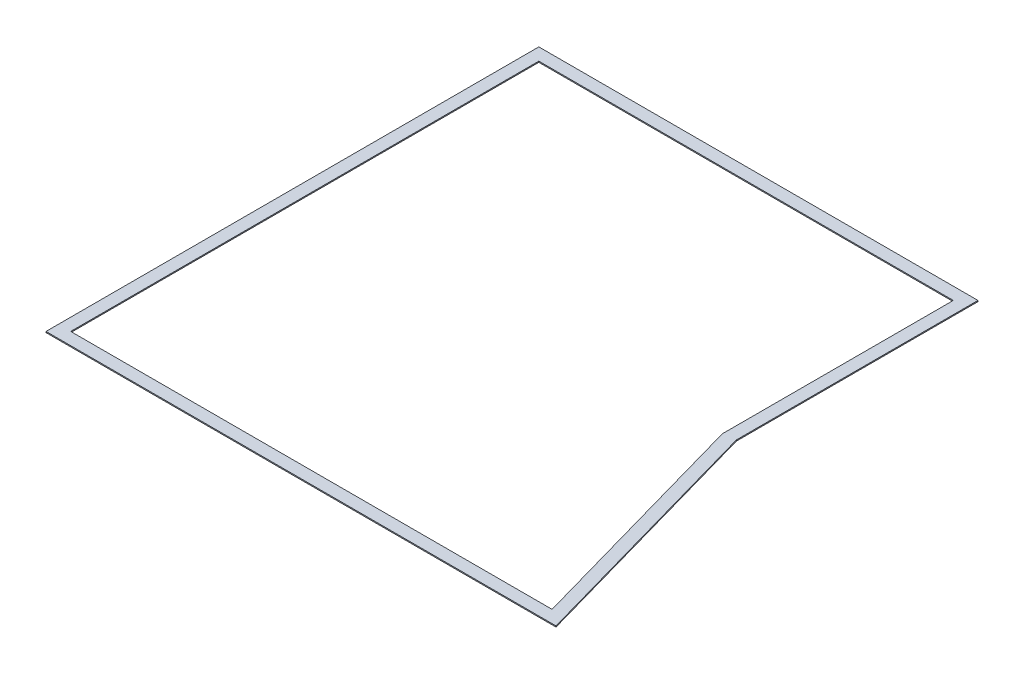
SolidWorks part; units mm, degrees
ref_plane "前视基准面" through (0, 0, 0) normal (0, 0, 1) x (1, 0, 0)
ref_plane "上视基准面" through (0, 0, 0) normal (0, 1, 0) x (1, 0, 0)
ref_plane "右视基准面" through (0, 0, 0) normal (1, 0, 0) x (0, 0, -1)
sketch "草图1" plane through (0, 0, 0) normal (0, 1, 0) x (1, 0, 0)
  line L0 (-409, 458) -> (-409, -460)
  line L1 (-409, -460) -> (541, -460)
  line L2 (541, -460) -> (409, 8)
  line L3 (409, 8) -> (409, 458)
  line L4 (409, 458) -> (-409, 458)
  line L5 (386, 435) -> (-386, 435)
  line L6 (-386, 435) -> (-386, -437)
  line L7 (-386, -437) -> (510.6155, -437)
  line L8 (510.6155, -437) -> (386, 4.8185)
  line L9 (386, 4.8185) -> (386, 435)
  dimension "D1" = 918
  dimension "D2" = 818
  dimension "D3" = 450
  dimension "D4" = 950
  dimension "D5" = 458
  dimension "D6" = 409
  dimension "D7" = 23
extrude "凸台-拉伸1" add sketch "草图1" along normal blind 2
